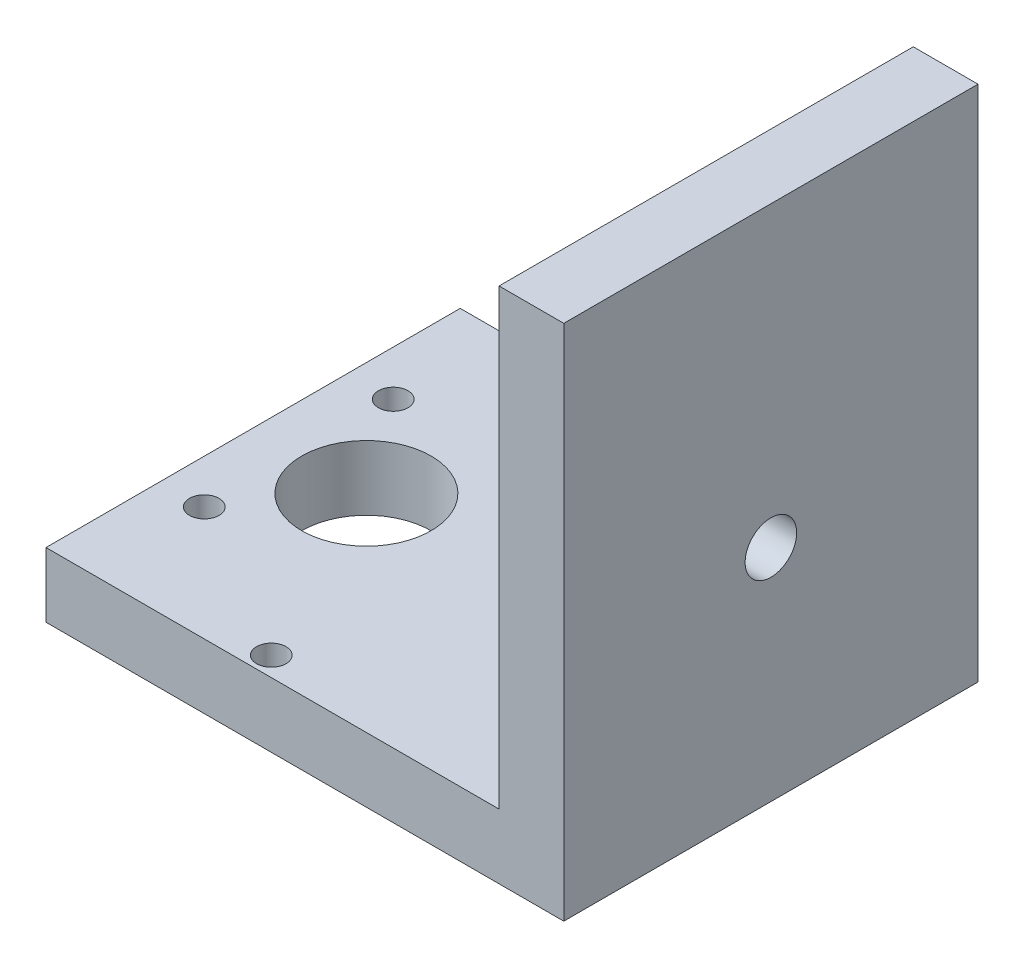
SolidWorks part; units mm, degrees
ref_plane "Front Plane" through (0, 0, 0) normal (0, 0, 1) x (1, 0, 0)
ref_plane "Top Plane" through (0, 0, 0) normal (0, 1, 0) x (1, 0, 0)
ref_plane "Right Plane" through (0, 0, 0) normal (1, 0, 0) x (0, 0, -1)
sketch "Sketch4" plane through (0, 0, 0) normal (0, 0, 1) x (1, 0, 0)
  line L1 (14.3007, 21.994) -> (20.6507, 21.994)
  line L2 (14.3007, 21.994) -> (14.3007, -22.456)
  line L3 (9.2239, -28.806) -> (20.6507, -28.806)
  line L4 (20.6507, 21.994) -> (20.6507, -28.806)
  line L5 (9.2239, -28.806) -> (-30.1493, -28.806)
  line L7 (14.3007, -22.456) -> (-30.1493, -22.456)
  line L8 (-30.1493, -28.806) -> (-30.1493, -22.456)
  dimension "D1" = 50.8
  dimension "D2" = 6.35
  dimension "D3" = 6.35
  dimension "D4" = 50.8
extrude "Boss-Extrude1" add sketch "Sketch4" along normal blind 40.64
hole_wizard "#8 (0.199) Diameter Hole1" positions "Sketch5" profile "Sketch6" hole size "#8" standard "ANSI Inch" end condition through all
sketch "Sketch5" plane through (20.6507, 0, 0) normal (1, 0, 0) x (0, 0, -1)
  line L0 (-40.64, -28.806) -> (0, -28.806) construction
  line L1 (0, -28.806) -> (0, 21.994) construction
  point P0 (-20.32, -7.216)
  dimension "D1" = 21.59
  dimension "D2" = 20.32
sketch "Sketch6" plane through (20.6507, -7.216, 20.32) normal (0, 1, 0) x (0, 0, -1)
  line L0 (0, 0) -> (0, 50.8)
  line L1 (0, 50.8) -> (2.5273, 50.8)
  line L2 (2.5273, 50.8) -> (2.5273, 0)
  line L5 (2.5273, 0) -> (0, 0)
  line L11 (0, -6.35) -> (0, 107.95) construction
  dimension "Thru Hole Dia." = 5.0546
  dimension "Thru Hole Depth" = 50.8
sketch "Sketch7" plane through (0, -22.456, 0) normal (0, 1, 0) x (1, 0, 0)
  line L0 (14.3007, 0) -> (-30.1493, 0) construction
  circle A0 centre (-19.0338, -20.32) radius 6.35
  dimension "D1" = 12.7
  dimension "D2" = 20.32
extrude "Cut-Extrude1" cut sketch "Sketch7" against normal blind 40.64
sketch "Sketch8" plane through (0, -22.456, 0) normal (0, 1, 0) x (1, 0, 0)
  line L0 (14.3007, 0) -> (-30.1493, 0) construction
  line L1 (-30.1493, -40.64) -> (-30.1493, 0) construction
  circle A0 centre (-9.8293, -20.32) radius 18.415
  dimension "D2" = 36.83
  dimension "D1" = 20.32
  dimension "D3" = 20.32
hole_wizard "Tap Drill for M3.5x0.6 Tap1" positions "Sketch9" profile "Sketch10" hole size "M3.5x0.6" standard "ANSI Metric" end condition through all
sketch "Sketch9" plane through (0, -22.456, 0) normal (0, 1, 0) x (1, 0, 0)
  circle A0 centre (-9.8293, -20.32) radius 18.415 construction
  point P0 (-25.7158, -11.0071)
  point P4 (-25.8377, -29.4217)
  point P6 (-9.9512, -38.7346)
  point P8 (-9.7073, -1.9054)
  point P10 (6.1792, -11.2183)
  point P14 (6.0573, -29.6329)
  dimension "D1" = 60
  dimension "D2" = 60
  dimension "D3" = 60
  dimension "D4" = 60
  dimension "D5" = 60
sketch "Sketch10" plane through (-25.7158, -22.456, 11.0071) normal (1, 0, 0) x (0, 0, 1)
  line L0 (0, 0) -> (0, 6.35)
  line L1 (0, 6.35) -> (1.45, 6.35)
  line L2 (1.45, 6.35) -> (1.45, 0)
  line L5 (1.45, 0) -> (0, 0)
  line L11 (0, -6.35) -> (0, 107.95) construction
  dimension "Thru Hole Dia." = 2.9
  dimension "Thru Hole Depth" = 6.35
